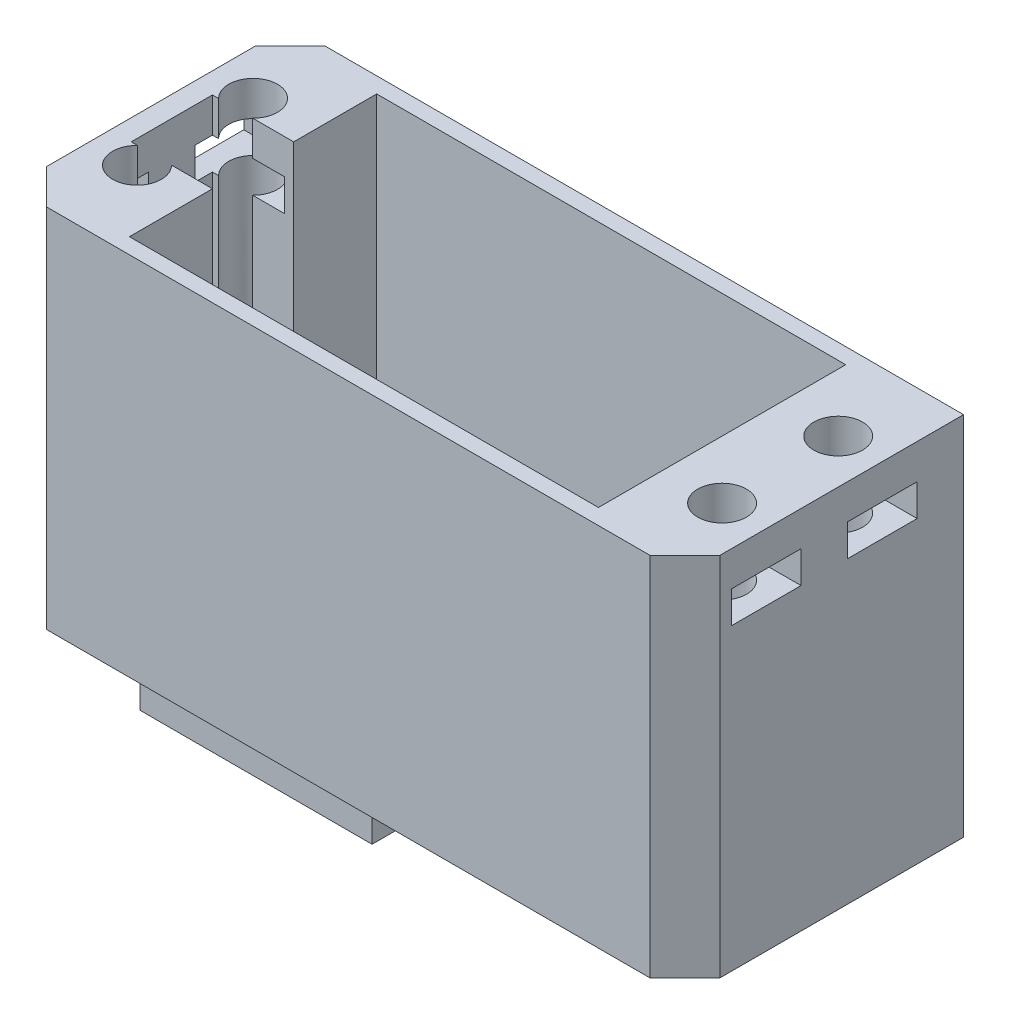
SolidWorks part; units mm, degrees
ref_plane "Front Plane" through (0, 0, 0) normal (0, 0, 1) x (1, 0, 0)
ref_plane "Top Plane" through (0, 0, 0) normal (0, 1, 0) x (1, 0, 0)
ref_plane "Right Plane" through (0, 0, 0) normal (1, 0, 0) x (0, 0, -1)
sketch "Sketch1" plane through (0, 0, 0) normal (0, 1, 0) x (1, 0, 0)
  line L0 (9.75, 1.0273) -> (50.15, 1.0273)
  line L1 (50.15, 1.0273) -> (50.15, -20.2727)
  line L2 (50.15, -20.2727) -> (9.75, -20.2727)
  line L4 (0.95, -21.6227) -> (58.95, -21.6227)
  line L5 (58.95, -21.6227) -> (58.95, 2.3773)
  line L6 (58.95, 2.3773) -> (0.95, 2.3773)
  line L8 (55.15, -4.6227) -> (55.15, -14.6227) construction
  line L9 (0.95, 2.3773) -> (0.95, -21.6227)
  line L10 (9.75, 1.0273) -> (9.75, -20.2727)
  line L11 (29.95, 1.0273) -> (29.95, -20.2727) construction
  circle A0 centre (55.15, -4.6227) radius 2.1
  circle A1 centre (55.15, -14.6227) radius 2.1
  circle A2 centre (4.75, -14.6227) radius 2.1
  circle A3 centre (4.75, -4.6227) radius 2.1
  point P13 (55.15, -9.6227)
  point P14 (50.15, -9.6227)
  point P20 (0.95, -9.6227)
  point P22 (29.95, 2.3773)
  dimension "D1" = 4.2
  dimension "D2" = 10
  dimension "D3" = 24
  dimension "D4" = 40.4
  dimension "D5" = 5
  dimension "D6" = 21.3
  dimension "D7" = 58
extrude "Boss-Extrude1" add sketch "Sketch1" along normal blind 28.35
sketch "Sketch11" plane through (0, 0, 0) normal (0, -1, 0) x (1, 0, 0)
  line L1 (0.95, 21.6227) -> (58.95, 21.6227)
  line L2 (0.95, 21.6227) -> (0.95, -2.3773)
  line L3 (0.95, -2.3773) -> (58.95, -2.3773)
  line L4 (58.95, 21.6227) -> (58.95, -2.3773)
extrude "Boss-Extrude5" add sketch "Sketch11" along normal blind 3.175
sketch "Sketch14" plane through (0, 0, -2.3773) normal (0, 0, -1) x (-1, 0, 0)
  line L0 (-0.95, 28.35) -> (-0.95, -3.175) construction
  line L8 (-0.95, 6.5875) -> (-24.95, 6.5875)
  line L9 (-0.95, 6.5875) -> (-0.95, 18.5875)
  line L10 (-0.95, 18.5875) -> (-24.95, 18.5875)
  line L11 (-24.95, 6.5875) -> (-24.95, 18.5875)
  line L12 (-0.95, 6.5875) -> (-24.95, 18.5875) construction
  line L13 (-0.95, 18.5875) -> (-24.95, 6.5875) construction
  point P0 (-12.95, 12.5875)
  point P5 (-12.95, 12.5875)
  point P6 (-0.95, 12.5875)
  dimension "D1" = 24
  dimension "D2" = 12
  dimension "D3" = 0
extrude "Boss-Extrude7" add sketch "Sketch14" along normal blind 10
ref_plane "Plane1" through (0, 0, -7.3773) normal (0, 0, -1) x (-1, 0, 0)
sketch "Sketch16" plane through (0, 0, -7.3773) normal (0, 0, -1) x (-1, 0, 0)
  line L1 (-11.45, 16.7875) -> (-24.95, 16.7875)
  line L3 (-11.45, 8.3875) -> (-24.95, 8.3875)
  line L4 (-24.95, 16.7875) -> (-24.95, 8.3875)
  line L6 (-24.95, 18.5875) -> (-24.95, 6.5875) construction
  arc A0 (-11.45, 8.3875) -> (-11.45, 16.7875) centre (-11.45, 12.5875) ccw
  point P10 (-24.95, 12.5875)
  dimension "D2" = 4.2
  dimension "D1" = 13.5
extrude "Cut-Extrude1" cut sketch "Sketch16" against normal mid plane 7.6
fillet "Fillet1" radius 8 2 edges at (12.95, 6.5875, -2.3773) (12.95, 18.5875, -2.3773)
chamfer "Chamfer2" distance 3 angle 45 8 edges at (0.95, 27.4688, -2.3773) (0.95, -2.2938, -2.3773) (0.95, 12.5875, 21.6227) (58.95, 12.5875, 21.6227) (0.95, 18.5875, -11.3773) (0.95, 20.9306, -4.7205) (0.95, 6.5875, -11.3773) (0.95, 4.2444, -4.7205)
chamfer "Chamfer3" distance 1 angle 45 4 edges at (14.45, 6.5875, -12.3773) (24.95, 12.5875, -12.3773) (14.45, 18.5875, -12.3773) (0.95, 12.5875, -12.3773)
ref_plane "Plane2" through (0, 25.35, 0) normal (0, 1, 0) x (1, 0, 0)
sketch "Sketch19" plane through (0, 25.35, 0) normal (0, 1, 0) x (1, 0, 0)
  line L0 (0.95, -0.6227) -> (0.95, -18.6227) construction
  line L1 (0.95, -1.6227) -> (8.95, -1.6227)
  line L2 (0.95, -1.6227) -> (0.95, -7.6227)
  line L3 (0.95, -7.6227) -> (8.95, -7.6227)
  line L4 (8.95, -1.6227) -> (8.95, -7.6227)
  line L5 (-0.5892, -9.6227) -> (60.8708, -9.6227) construction
  line L6 (29.95, -22.0073) -> (29.95, 3.0189) construction
  line L7 (9.75, 1.0273) -> (9.75, -20.2727) construction
  line L8 (50.15, 1.0273) -> (9.75, 1.0273) construction
  line L9 (8.95, -17.6227) -> (8.95, -11.6227)
  line L10 (0.95, -11.6227) -> (8.95, -11.6227)
  line L11 (0.95, -17.6227) -> (0.95, -11.6227)
  line L12 (0.95, -17.6227) -> (8.95, -17.6227)
  line L37 (60.4892, -9.6227) -> (-0.9708, -9.6227) construction
  line L38 (58.95, -17.6227) -> (50.95, -17.6227)
  line L39 (58.95, -17.6227) -> (58.95, -11.6227)
  line L40 (58.95, -11.6227) -> (50.95, -11.6227)
  line L41 (50.95, -17.6227) -> (50.95, -11.6227)
  line L42 (50.95, -1.6227) -> (50.95, -7.6227)
  line L43 (58.95, -7.6227) -> (50.95, -7.6227)
  line L44 (58.95, -1.6227) -> (58.95, -7.6227)
  line L45 (58.95, -1.6227) -> (50.95, -1.6227)
  circle A0 centre (4.75, -4.6227) radius 2.1 construction
  circle A1 centre (4.75, -4.6227) radius 2.1 construction
  circle A2 centre (4.75, -14.6227) radius 2.1 construction
  circle A3 centre (4.75, -4.6227) radius 2.1 construction
  circle A4 centre (4.75, -14.6227) radius 2.1 construction
  circle A5 centre (4.75, -4.6227) radius 2.1 construction
  circle A6 centre (4.75, -14.6227) radius 2.1 construction
  circle A7 centre (4.75, -4.6227) radius 2.1 construction
  circle A8 centre (4.75, -14.6227) radius 2.1 construction
  circle A9 centre (55.15, -14.6227) radius 2.1 construction
  circle A10 centre (55.15, -4.6227) radius 2.1 construction
  circle A11 centre (55.15, -14.6227) radius 2.1 construction
  circle A12 centre (55.15, -4.6227) radius 2.1 construction
  circle A13 centre (55.15, -14.6227) radius 2.1 construction
  circle A14 centre (55.15, -4.6227) radius 2.1 construction
  circle A15 centre (55.15, -14.6227) radius 2.1 construction
  circle A16 centre (55.15, -4.6227) radius 2.1 construction
  point P11 (0.95, -4.6227)
  point P18 (9.75, -9.6227)
  point P21 (29.95, 1.0273)
  point P28 (0.95, -14.6227)
  point P55 (58.95, -14.6227)
  point P56 (58.95, -4.6227)
  dimension "D1" = 6
  dimension "D2" = 8
extrude "Cut-Extrude3" cut sketch "Sketch19" against normal blind 2.75
sketch "Sketch20" plane through (0, 0, 0) normal (0, 1, 0) x (1, 0, 0)
  line L0 (0.95, -0.6227) -> (0.95, -18.6227) construction
  line L1 (0.95, -13.8727) -> (9.75, -13.8727)
  line L2 (0.95, -13.8727) -> (0.95, -5.3727)
  line L3 (0.95, -5.3727) -> (9.75, -5.3727)
  line L4 (9.75, -13.8727) -> (9.75, -5.3727)
  line L5 (9.75, 1.0273) -> (9.75, -20.2727) construction
  point P6 (0.95, -9.6227)
  dimension "D1" = 8.5
extrude "Cut-Extrude4" cut sketch "Sketch20" along normal blind 4
sketch "Sketch21" plane through (0, -3.175, 0) normal (0, -1, 0) x (1, 0, 0)
  line L0 (0.95, 18.6227) -> (0.95, 0.6227) construction
  line L1 (30, -0.3773) -> (10, -0.3773)
  line L2 (30, -0.3773) -> (30, 19.6227)
  line L3 (30, 19.6227) -> (10, 19.6227)
  line L4 (10, -0.3773) -> (10, 19.6227)
  line L5 (30, -0.3773) -> (10, 19.6227) construction
  line L6 (30, 19.6227) -> (10, -0.3773) construction
  point P0 (20, 9.6227)
  point P7 (0.95, 9.6227)
  dimension "D1" = 19.05
  dimension "D2" = 20
  dimension "D3" = 20
extrude "Boss-Extrude8" add sketch "Sketch21" along normal blind 6
sketch "Sketch13" plane through (0, -9.175, 0) normal (0, -1, 0) x (1, 0, 0)
  line L0 (0.95, 18.6227) -> (0.95, 0.6227) construction
  circle A0 centre (20, 9.6227) radius 2.55
  point P2 (0.95, 9.6227)
  dimension "D2" = 5.1
  dimension "D1" = 19.05
extrude "Boss-Extrude6" add sketch "Sketch13" along normal blind 5
fillet "Fillet4" radius 1 4 edges at (20, -3.175, 19.6227) (30, -3.175, 9.6227) (20, -3.175, -0.3773) (10, -3.175, 9.6227)
chamfer "Chamfer4" distance 2 angle 45 4 edges at (20, -9.175, 19.6227) (30, -9.175, 9.6227) (20, -9.175, -0.3773) (10, -9.175, 9.6227)
fillet "Fillet5" radius 1 1 edges at (20, -14.175, 7.0727)
sketch "Sketch22" plane through (0, 28.35, 0) normal (0, 1, 0) x (1, 0, 0)
  line L0 (9.75, 1.0273) -> (9.75, -20.2727) construction
  line L2 (9.75, -6.1227) -> (2.75, -6.1227)
  line L3 (9.75, -6.1227) -> (9.75, -13.1227)
  line L4 (9.75, -13.1227) -> (2.75, -13.1227)
  line L5 (2.75, -6.1227) -> (2.75, -13.1227)
  point P0 (9.75, -9.6227)
  dimension "D1" = 7
  dimension "D2" = 7
extrude "Cut-Extrude5" cut sketch "Sketch22" against normal up to surface (28.35 mm away) up to face at (55.15, 0, 16.7227)
